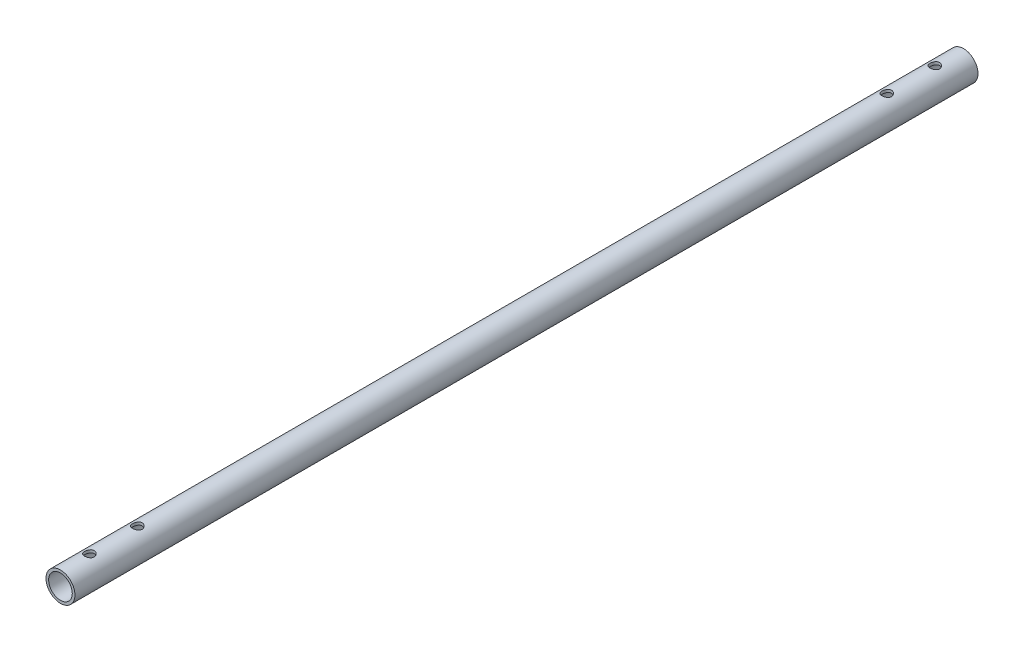
SolidWorks part; units mm, degrees
material "CK45"
ref_plane "Front Plane" through (0, 0, 0) normal (0, 0, 1) x (1, 0, 0)
ref_plane "Top Plane" through (0, 0, 0) normal (0, 1, 0) x (1, 0, 0)
ref_plane "Right Plane" through (0, 0, 0) normal (1, 0, 0) x (0, 0, -1)
sketch "Sketch1" plane through (0, 0, 0) normal (0, 0, 1) x (1, 0, 0)
  circle A0 centre (0, 0) radius 30.15
  dimension "D1" = 60.3
extrude "Extrude-Thin1" add sketch "Sketch1" along normal mid plane 1880 thin thin type one direction reverse wall 5.54
sketch "Sketch2" plane through (0, 0, 0) normal (0, 1, 0) x (1, 0, 0)
  line L0 (24.61, 940) -> (-24.61, 940) construction
  line L1 (0, 940) -> (0, 699.6614) construction
  line L2 (30.15, 940) -> (-30.15, 940) construction
  circle A0 centre (0, 880) radius 10.05
  circle A1 centre (0, 780) radius 10.05
  dimension "D1" = 20.1
  dimension "D2" = 60
  dimension "D3" = 100
extrude "Cut-Extrude1" cut sketch "Sketch2" against normal through all both and the other way through all
mirror "Mirror1" about plane through (0, 0, 0) normal (0, 0, 1) of "Cut-Extrude1"
